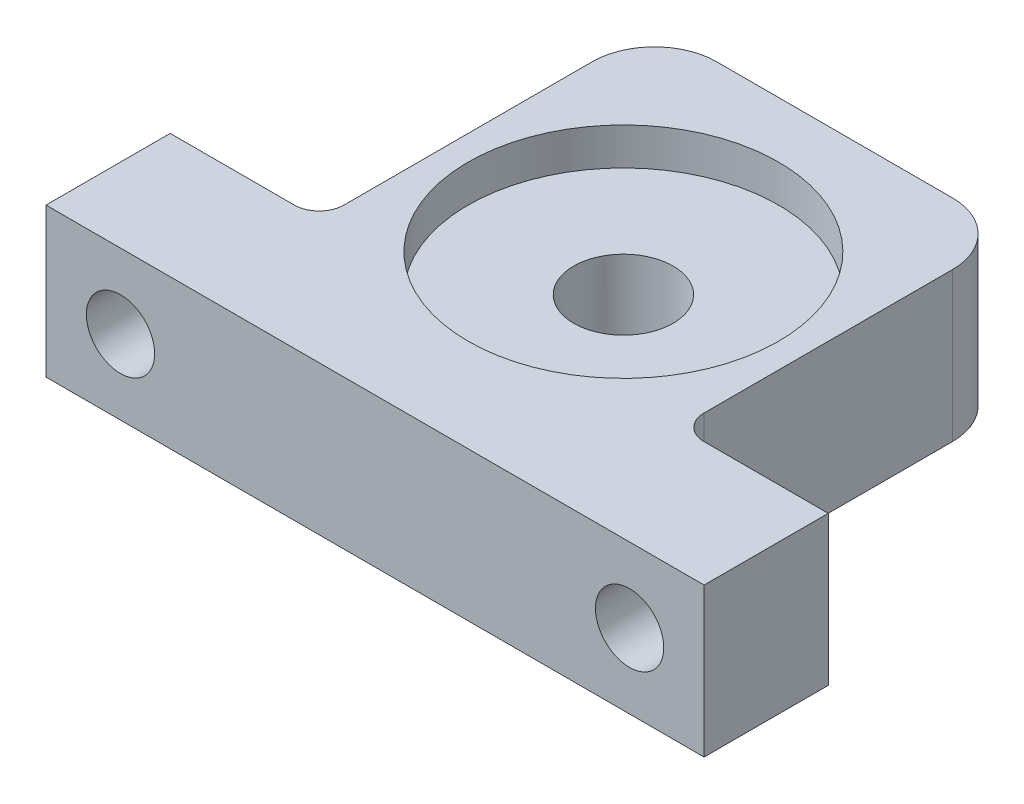
SolidWorks part; units mm, degrees
ref_plane "前视基准面" through (0, 0, 0) normal (0, 0, 1) x (1, 0, 0)
ref_plane "上视基准面" through (0, 0, 0) normal (0, 1, 0) x (1, 0, 0)
ref_plane "右视基准面" through (0, 0, 0) normal (1, 0, 0) x (0, 0, -1)
sketch "草图1" plane through (0, 0, 0) normal (0, 1, 0) x (1, 0, 0)
  line L0 (14.5, 5) -> (26.5, 5)
  line L1 (-26.5, -5) -> (26.5, -5)
  line L2 (-26.5, -5) -> (-26.5, 5)
  line L3 (-26.5, 5) -> (-14.5, 5)
  line L4 (26.5, -5) -> (26.5, 5)
  line L5 (-26.5, -5) -> (26.5, 5) construction
  line L6 (-26.5, 5) -> (26.5, -5) construction
  line L7 (-9.5, 32) -> (9.5, 32)
  line L8 (-14.5, 27) -> (-14.5, 5)
  line L10 (14.5, 27) -> (14.5, 5)
  line L11 (-14.5, 32) -> (14.5, 5) construction
  line L12 (-14.5, 5) -> (14.5, 32) construction
  arc A0 (14.5, 27) -> (9.5, 32) centre (9.5, 27) ccw
  arc A1 (-9.5, 32) -> (-14.5, 27) centre (-9.5, 27) ccw
  point P0 (0, 0)
  point P6 (0, 18.5)
  dimension "D5" = 5
  dimension "D1" = 53
  dimension "D2" = 29
  dimension "D3" = 10
  dimension "D4" = 37
extrude "凸台-拉伸1" add sketch "草图1" along normal mid plane 12
fillet "圆角1" radius 2 2 edges at (14.5, 0, -5) (-14.5, 0, -5)
sketch "草图2" plane through (0, 0, -5) normal (0, 0, -1) x (-1, 0, 0)
  line L0 (0, 0) -> (0, 50000) construction
  circle A0 centre (20.5, 0) radius 2.75
  circle A1 centre (-20.5, 0) radius 2.75
  dimension "D1" = 5.5
  dimension "D2" = 41
extrude "切除-拉伸1" cut sketch "草图2" against normal mid plane 280
sketch "草图3" plane through (0, -6, 0) normal (0, -1, 0) x (1, 0, 0)
  line L0 (-26.5, 5) -> (26.5, 5) construction
  circle A0 centre (0, -15) radius 9
  dimension "D2" = 18
  dimension "D1" = 20
extrude "切除-拉伸2" cut sketch "草图3" against normal blind 2
sketch "草图5" plane through (0, 6, 0) normal (0, 1, 0) x (1, 0, 0)
  line L0 (-26.5, -5) -> (26.5, -5) construction
  circle A0 centre (0, 15) radius 12.5
  dimension "D1" = 25
  dimension "D2" = 20
extrude "切除-拉伸4" cut sketch "草图5" against normal blind 3
sketch "草图6" plane through (0, 3, 0) normal (0, 1, 0) x (1, 0, 0)
  circle A0 centre (0, 15) radius 4
  dimension "D1" = 8
extrude "切除-拉伸5" cut sketch "草图6" against normal blind 76
